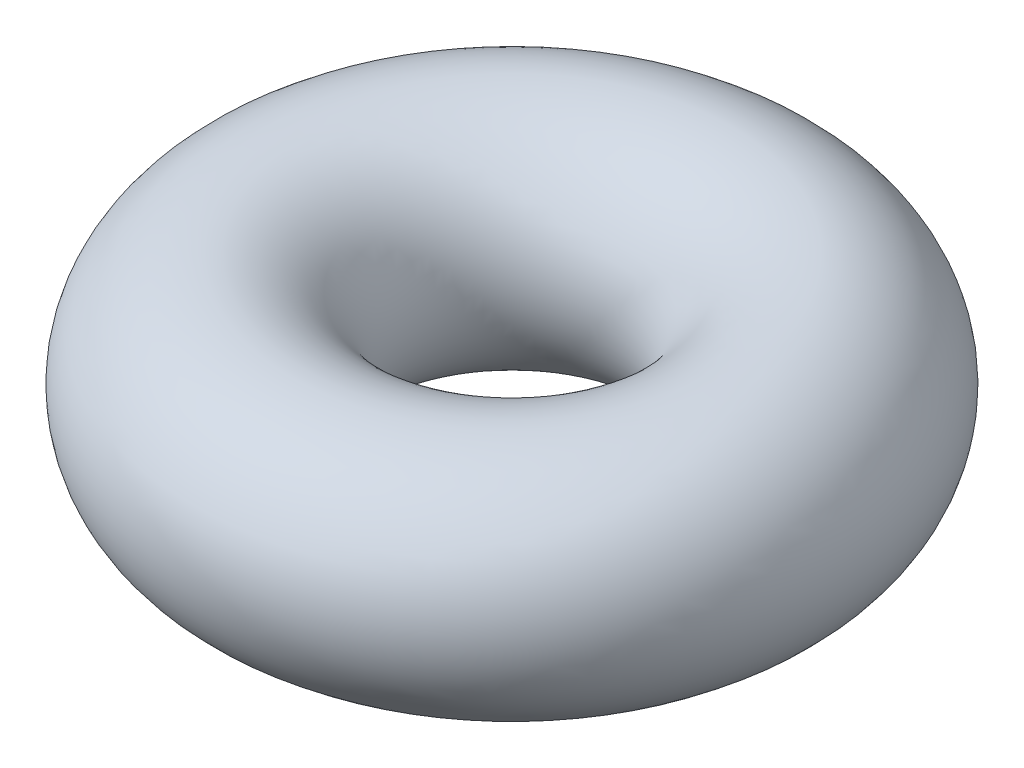
SolidWorks part; units mm, degrees
ref_plane "Front Plane" through (0, 0, 0) normal (0, 0, 1) x (1, 0, 0)
ref_plane "Top Plane" through (0, 0, 0) normal (0, 1, 0) x (1, 0, 0)
ref_plane "Right Plane" through (0, 0, 0) normal (1, 0, 0) x (0, 0, -1)
sketch "Sketch3" plane through (0, 0, 0) normal (1, 0, 0) x (0, 0, -1)
  line L0 (0, 0) -> (0, 66.7712)
  circle A0 centre (59.8387, 0) radius 21.8595
revolve "Revolve-Thin1" add sketch "Sketch3" angle 360 about L0
